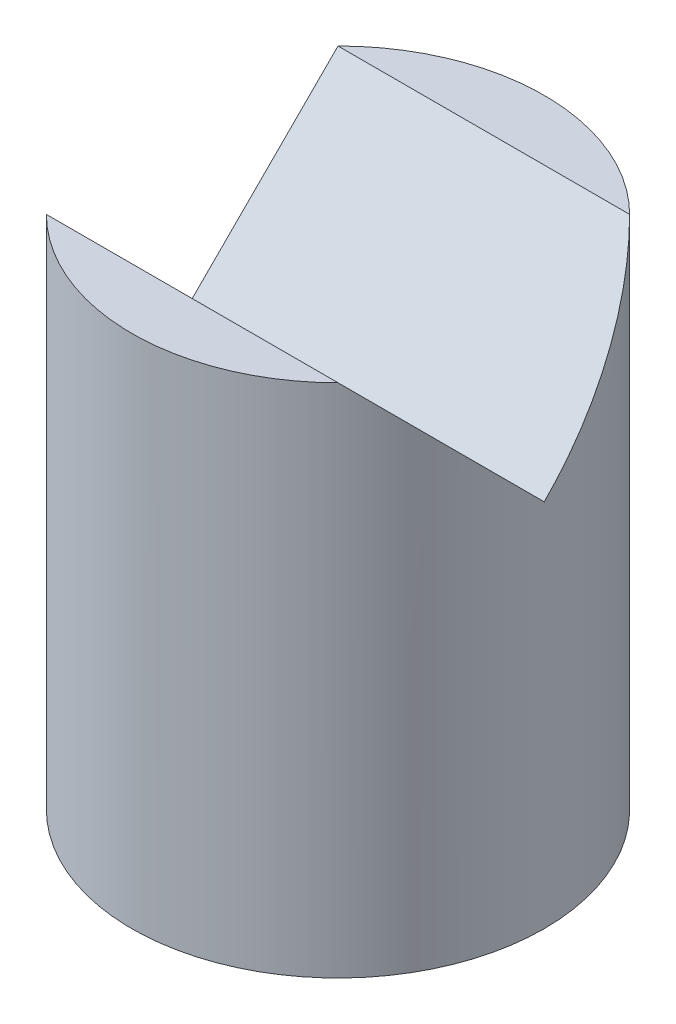
SolidWorks part; units mm, degrees
ref_plane "Front Plane" through (0, 0, 0) normal (0, 0, 1) x (1, 0, 0)
ref_plane "Top Plane" through (0, 0, 0) normal (0, 1, 0) x (1, 0, 0)
ref_plane "Right Plane" through (0, 0, 0) normal (1, 0, 0) x (0, 0, -1)
sketch "Sketch1" plane through (0, 0, 0) normal (0, 1, 0) x (1, 0, 0)
  line L0 (-2.8284, 2.8284) -> (-2.8284, -2.8284)
  line L1 (0, 0) -> (-2.8284, 2.8284) construction
  line L2 (0, 0) -> (-2.8284, -2.8284) construction
  arc A0 (-2.8284, 2.8284) -> (-2.8284, -2.8284) centre (0, 0) cw
  dimension "D1" = 90
  dimension "D2" = 4
extrude "Boss-Extrude1" add sketch "Sketch1" along normal blind 10
sketch "Sketch2" plane through (-2.8284, 0, 0) normal (-1, 0, 0) x (0, 0, 1)
  line L0 (-2.8284, 10) -> (0, 7.1716)
  line L1 (0, 7.1716) -> (2.8284, 10)
  line L2 (2.8284, 10) -> (-2.8284, 10)
extrude "Cut-Extrude1" cut sketch "Sketch2" against normal up to next
sketch "Sketch4" plane through (0, 0, 0) normal (1, 0, 0) x (0, 0, -1)
  line L0 (-2.8284, 10) -> (0, 7.1716) construction
  line L1 (0, 7.1716) -> (2.8284, 10) construction
  line L2 (2.8284, 0) -> (-2.8284, 0) construction
  line L3 (2.8284, 10) -> (0, 7.1716) construction
  line L4 (0, 7.1716) -> (-2.8284, 10) construction
  line L5 (-2.8284, 10) -> (-4, 10) construction
  line L6 (-4, 0) -> (4, 0) construction
  line L7 (4, 10) -> (2.8284, 10) construction
  line L8 (-2.8284, 10) -> (0, 7.1716)
  line L9 (0, 7.1716) -> (2.8284, 10)
  line L10 (2.8284, 0) -> (-2.8284, 0)
  line L11 (2.8284, 10) -> (0, 7.1716)
  line L12 (0, 7.1716) -> (-2.8284, 10)
  line L13 (-2.8284, 10) -> (-4, 10)
  line L14 (-4, 0) -> (4, 0)
  line L15 (4, 10) -> (2.8284, 10)
  line L16 (4, 10) -> (4, 0)
  line L17 (-4, 10) -> (-4, 0)
